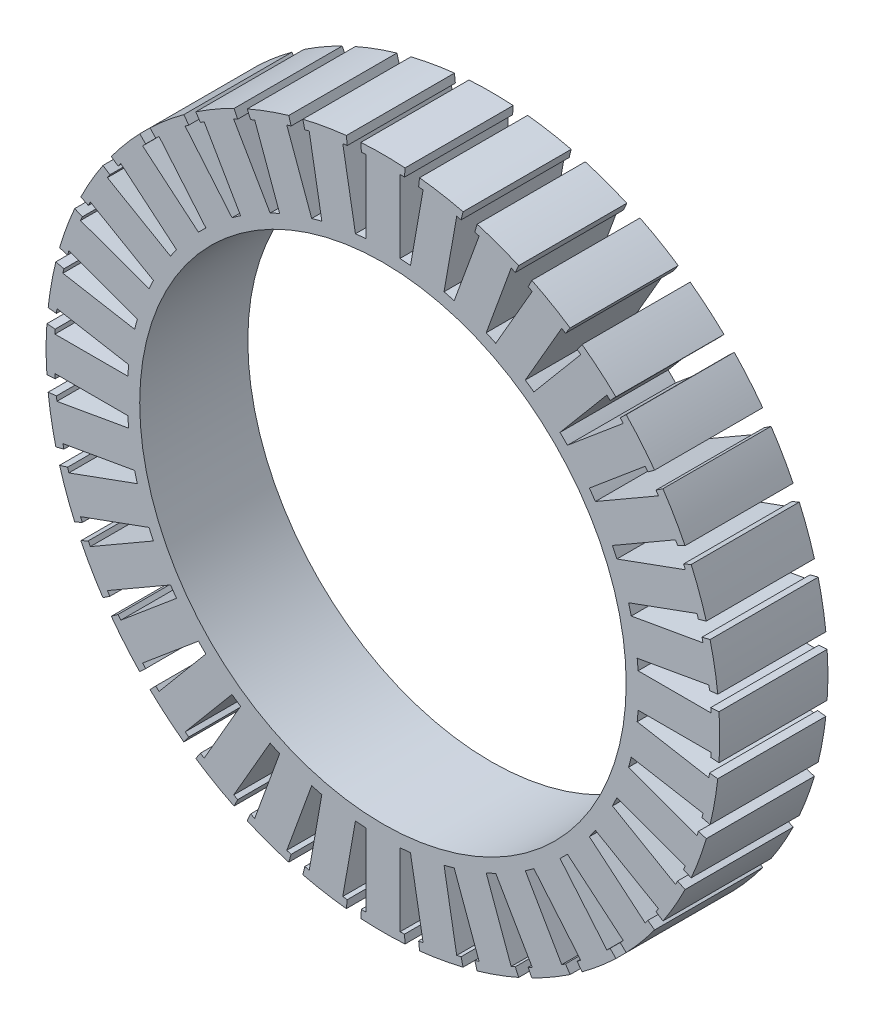
SolidWorks part; units mm, degrees
ref_plane "Front Plane" through (0, 0, 0) normal (0, 0, 1) x (1, 0, 0)
ref_plane "Top Plane" through (0, 0, 0) normal (0, 1, 0) x (1, 0, 0)
ref_plane "Right Plane" through (0, 0, 0) normal (1, 0, 0) x (0, 0, -1)
sketch "Sketch1" plane through (0, 0, 0) normal (0, 0, 1) x (1, 0, 0)
  line L0 (-2.6573, 40.4127) -> (0, 0) construction
  line L2 (-2.0508, 39.4467) -> (-2.0508, 29.178)
  line L3 (2.0508, 39.4467) -> (2.0508, 29.178)
  line L4 (2.6573, 40.4127) -> (0, 0) construction
  line L5 (-2.6573, 40.4127) -> (-2.5917, 39.4149)
  line L6 (2.6573, 40.4127) -> (2.5917, 39.4149)
  line L7 (9.6345, 39.3373) -> (9.3966, 38.366)
  line L8 (4.4007, 40.2602) -> (4.292, 39.2661)
  line L9 (4.8302, 39.2036) -> (3.047, 29.0909)
  line L10 (8.8695, 38.4913) -> (7.0864, 28.3786)
  line L11 (16.319, 37.0667) -> (15.9161, 36.1515)
  line L12 (11.3249, 38.8844) -> (11.0453, 37.9243)
  line L13 (11.5644, 37.7692) -> (8.0523, 28.1198)
  line L14 (15.4187, 36.3664) -> (11.9066, 26.7169)
  line L15 (22.5077, 33.6698) -> (21.9519, 32.8384)
  line L16 (17.9051, 36.3271) -> (17.463, 35.4301)
  line L17 (17.9473, 35.1873) -> (12.8129, 26.2943)
  line L18 (21.4994, 33.1364) -> (16.3651, 24.2435)
  line L19 (28.0124, 29.2499) -> (27.3208, 28.5276)
  line L20 (23.9412, 32.666) -> (23.35, 31.8595)
  line L21 (23.7848, 31.5362) -> (17.1842, 23.6699)
  line L22 (26.9269, 28.8997) -> (20.3263, 21.0334)
  line L23 (32.666, 23.9412) -> (31.8595, 23.35)
  line L24 (29.2499, 28.0124) -> (28.5276, 27.3208)
  line L25 (28.8997, 26.9269) -> (21.0334, 20.3263)
  line L26 (31.5362, 23.7848) -> (23.6699, 17.1842)
  line L27 (36.3271, 17.9051) -> (35.4301, 17.463)
  line L28 (33.6698, 22.5077) -> (32.8384, 21.9519)
  line L29 (33.1364, 21.4994) -> (24.2435, 16.3651)
  line L30 (35.1873, 17.9473) -> (26.2943, 12.8129)
  line L31 (38.8844, 11.3249) -> (37.9243, 11.0453)
  line L32 (37.0667, 16.319) -> (36.1515, 15.9161)
  line L33 (36.3664, 15.4187) -> (26.7169, 11.9066)
  line L34 (37.7692, 11.5644) -> (28.1198, 8.0523)
  line L35 (40.2602, 4.4007) -> (39.2661, 4.292)
  line L36 (39.3373, 9.6345) -> (38.366, 9.3966)
  line L37 (38.4913, 8.8695) -> (28.3786, 7.0864)
  line L38 (39.2036, 4.8302) -> (29.0909, 3.047)
  line L39 (40.4127, -2.6573) -> (39.4149, -2.5917)
  line L40 (40.4127, 2.6573) -> (39.4149, 2.5917)
  line L41 (39.4467, 2.0508) -> (29.178, 2.0508)
  line L42 (39.4467, -2.0508) -> (29.178, -2.0508)
  line L43 (39.3373, -9.6345) -> (38.366, -9.3966)
  line L44 (40.2602, -4.4007) -> (39.2661, -4.292)
  line L45 (39.2036, -4.8302) -> (29.0909, -3.047)
  line L46 (38.4913, -8.8695) -> (28.3786, -7.0864)
  line L47 (37.0667, -16.319) -> (36.1515, -15.9161)
  line L48 (38.8844, -11.3249) -> (37.9243, -11.0453)
  line L49 (37.7692, -11.5644) -> (28.1198, -8.0523)
  line L50 (36.3664, -15.4187) -> (26.7169, -11.9066)
  line L51 (33.6698, -22.5077) -> (32.8384, -21.9519)
  line L52 (36.3271, -17.9051) -> (35.4301, -17.463)
  line L53 (35.1873, -17.9473) -> (26.2943, -12.8129)
  line L54 (33.1364, -21.4994) -> (24.2435, -16.3651)
  line L55 (29.2499, -28.0124) -> (28.5276, -27.3208)
  line L56 (32.666, -23.9412) -> (31.8595, -23.35)
  line L57 (31.5362, -23.7848) -> (23.6699, -17.1842)
  line L58 (28.8997, -26.9269) -> (21.0334, -20.3263)
  line L59 (23.9412, -32.666) -> (23.35, -31.8595)
  line L60 (28.0124, -29.2499) -> (27.3208, -28.5276)
  line L61 (26.9269, -28.8997) -> (20.3263, -21.0334)
  line L62 (23.7848, -31.5362) -> (17.1842, -23.6699)
  line L63 (17.9051, -36.3271) -> (17.463, -35.4301)
  line L64 (22.5077, -33.6698) -> (21.9519, -32.8384)
  line L65 (21.4994, -33.1364) -> (16.3651, -24.2435)
  line L66 (17.9473, -35.1873) -> (12.8129, -26.2943)
  line L67 (11.3249, -38.8844) -> (11.0453, -37.9243)
  line L68 (16.319, -37.0667) -> (15.9161, -36.1515)
  line L69 (15.4187, -36.3664) -> (11.9066, -26.7169)
  line L70 (11.5644, -37.7692) -> (8.0523, -28.1198)
  line L71 (4.4007, -40.2602) -> (4.292, -39.2661)
  line L72 (9.6345, -39.3373) -> (9.3966, -38.366)
  line L73 (8.8695, -38.4913) -> (7.0864, -28.3786)
  line L74 (4.8302, -39.2036) -> (3.047, -29.0909)
  line L75 (-2.6573, -40.4127) -> (-2.5917, -39.4149)
  line L76 (2.6573, -40.4127) -> (2.5917, -39.4149)
  line L77 (2.0508, -39.4467) -> (2.0508, -29.178)
  line L78 (-2.0508, -39.4467) -> (-2.0508, -29.178)
  line L79 (-9.6345, -39.3373) -> (-9.3966, -38.366)
  line L80 (-4.4007, -40.2602) -> (-4.292, -39.2661)
  line L81 (-4.8302, -39.2036) -> (-3.047, -29.0909)
  line L82 (-8.8695, -38.4913) -> (-7.0864, -28.3786)
  line L83 (-16.319, -37.0667) -> (-15.9161, -36.1515)
  line L84 (-11.3249, -38.8844) -> (-11.0453, -37.9243)
  line L85 (-11.5644, -37.7692) -> (-8.0523, -28.1198)
  line L86 (-15.4187, -36.3664) -> (-11.9066, -26.7169)
  line L87 (-22.5077, -33.6698) -> (-21.9519, -32.8384)
  line L88 (-17.9051, -36.3271) -> (-17.463, -35.4301)
  line L89 (-17.9473, -35.1873) -> (-12.8129, -26.2943)
  line L90 (-21.4994, -33.1364) -> (-16.3651, -24.2435)
  line L91 (-28.0124, -29.2499) -> (-27.3208, -28.5276)
  line L92 (-23.9412, -32.666) -> (-23.35, -31.8595)
  line L93 (-23.7848, -31.5362) -> (-17.1842, -23.6699)
  line L94 (-26.9269, -28.8997) -> (-20.3263, -21.0334)
  line L95 (-32.666, -23.9412) -> (-31.8595, -23.35)
  line L96 (-29.2499, -28.0124) -> (-28.5276, -27.3208)
  line L97 (-28.8997, -26.9269) -> (-21.0334, -20.3263)
  line L98 (-31.5362, -23.7848) -> (-23.6699, -17.1842)
  line L99 (-36.3271, -17.9051) -> (-35.4301, -17.463)
  line L100 (-33.6698, -22.5077) -> (-32.8384, -21.9519)
  line L101 (-33.1364, -21.4994) -> (-24.2435, -16.3651)
  line L102 (-35.1873, -17.9473) -> (-26.2943, -12.8129)
  line L103 (-38.8844, -11.3249) -> (-37.9243, -11.0453)
  line L104 (-37.0667, -16.319) -> (-36.1515, -15.9161)
  line L105 (-36.3664, -15.4187) -> (-26.7169, -11.9066)
  line L106 (-37.7692, -11.5644) -> (-28.1198, -8.0523)
  line L107 (-40.2602, -4.4007) -> (-39.2661, -4.292)
  line L108 (-39.3373, -9.6345) -> (-38.366, -9.3966)
  line L109 (-38.4913, -8.8695) -> (-28.3786, -7.0864)
  line L110 (-39.2036, -4.8302) -> (-29.0909, -3.047)
  line L111 (-40.4127, 2.6573) -> (-39.4149, 2.5917)
  line L112 (-40.4127, -2.6573) -> (-39.4149, -2.5917)
  line L113 (-39.4467, -2.0508) -> (-29.178, -2.0508)
  line L114 (-39.4467, 2.0508) -> (-29.178, 2.0508)
  line L115 (-39.3373, 9.6345) -> (-38.366, 9.3966)
  line L116 (-40.2602, 4.4007) -> (-39.2661, 4.292)
  line L117 (-39.2036, 4.8302) -> (-29.0909, 3.047)
  line L118 (-38.4913, 8.8695) -> (-28.3786, 7.0864)
  line L119 (-37.0667, 16.319) -> (-36.1515, 15.9161)
  line L120 (-38.8844, 11.3249) -> (-37.9243, 11.0453)
  line L121 (-37.7692, 11.5644) -> (-28.1198, 8.0523)
  line L122 (-36.3664, 15.4187) -> (-26.7169, 11.9066)
  line L123 (-33.6698, 22.5077) -> (-32.8384, 21.9519)
  line L124 (-36.3271, 17.9051) -> (-35.4301, 17.463)
  line L125 (-35.1873, 17.9473) -> (-26.2943, 12.8129)
  line L126 (-33.1364, 21.4994) -> (-24.2435, 16.3651)
  line L127 (-29.2499, 28.0124) -> (-28.5276, 27.3208)
  line L128 (-32.666, 23.9412) -> (-31.8595, 23.35)
  line L129 (-31.5362, 23.7848) -> (-23.6699, 17.1842)
  line L130 (-28.8997, 26.9269) -> (-21.0334, 20.3263)
  line L131 (-23.9412, 32.666) -> (-23.35, 31.8595)
  line L132 (-28.0124, 29.2499) -> (-27.3208, 28.5276)
  line L133 (-26.9269, 28.8997) -> (-20.3263, 21.0334)
  line L134 (-23.7848, 31.5362) -> (-17.1842, 23.6699)
  line L135 (-17.9051, 36.3271) -> (-17.463, 35.4301)
  line L136 (-22.5077, 33.6698) -> (-21.9519, 32.8384)
  line L137 (-21.4994, 33.1364) -> (-16.3651, 24.2435)
  line L138 (-17.9473, 35.1873) -> (-12.8129, 26.2943)
  line L139 (-11.3249, 38.8844) -> (-11.0453, 37.9243)
  line L140 (-16.319, 37.0667) -> (-15.9161, 36.1515)
  line L141 (-15.4187, 36.3664) -> (-11.9066, 26.7169)
  line L142 (-11.5644, 37.7692) -> (-8.0523, 28.1198)
  line L143 (-4.4007, 40.2602) -> (-4.292, 39.2661)
  line L144 (-9.6345, 39.3373) -> (-9.3966, 38.366)
  line L145 (-8.8695, 38.4913) -> (-7.0864, 28.3786)
  line L146 (-4.8302, 39.2036) -> (-3.047, 29.0909)
  circle A0 centre (0, 0) radius 29.25 construction
  circle A1 centre (0, 0) radius 40.5 construction
  arc A2 (-2.6573, 40.4127) -> (2.6573, 40.4127) centre (0, 0) cw
  arc A3 (-2.0508, 29.178) -> (2.0508, 29.178) centre (0, 0) cw
  arc A4 (-2.5917, 39.4149) -> (-2.0508, 39.4467) centre (0, 0) cw
  arc A5 (2.0508, 39.4467) -> (2.5917, 39.4149) centre (0, 0) cw
  arc A6 (8.8695, 38.4913) -> (9.3966, 38.366) centre (0, 0) cw
  arc A7 (4.4007, 40.2602) -> (9.6345, 39.3373) centre (0, 0) cw
  arc A8 (4.292, 39.2661) -> (4.8302, 39.2036) centre (0, 0) cw
  arc A9 (3.047, 29.0909) -> (7.0864, 28.3786) centre (0, 0) cw
  arc A10 (15.4187, 36.3664) -> (15.9161, 36.1515) centre (0, 0) cw
  arc A11 (11.3249, 38.8844) -> (16.319, 37.0667) centre (0, 0) cw
  arc A12 (11.0453, 37.9243) -> (11.5644, 37.7692) centre (0, 0) cw
  arc A13 (8.0523, 28.1198) -> (11.9066, 26.7169) centre (0, 0) cw
  arc A14 (21.4994, 33.1364) -> (21.9519, 32.8384) centre (0, 0) cw
  arc A15 (17.9051, 36.3271) -> (22.5077, 33.6698) centre (0, 0) cw
  arc A16 (17.463, 35.4301) -> (17.9473, 35.1873) centre (0, 0) cw
  arc A17 (12.8129, 26.2943) -> (16.3651, 24.2435) centre (0, 0) cw
  arc A18 (26.9269, 28.8997) -> (27.3208, 28.5276) centre (0, 0) cw
  arc A19 (23.9412, 32.666) -> (28.0124, 29.2499) centre (0, 0) cw
  arc A20 (23.35, 31.8595) -> (23.7848, 31.5362) centre (0, 0) cw
  arc A21 (17.1842, 23.6699) -> (20.3263, 21.0334) centre (0, 0) cw
  arc A22 (31.5362, 23.7848) -> (31.8595, 23.35) centre (0, 0) cw
  arc A23 (29.2499, 28.0124) -> (32.666, 23.9412) centre (0, 0) cw
  arc A24 (28.5276, 27.3208) -> (28.8997, 26.9269) centre (0, 0) cw
  arc A25 (21.0334, 20.3263) -> (23.6699, 17.1842) centre (0, 0) cw
  arc A26 (35.1873, 17.9473) -> (35.4301, 17.463) centre (0, 0) cw
  arc A27 (33.6698, 22.5077) -> (36.3271, 17.9051) centre (0, 0) cw
  arc A28 (32.8384, 21.9519) -> (33.1364, 21.4994) centre (0, 0) cw
  arc A29 (24.2435, 16.3651) -> (26.2943, 12.8129) centre (0, 0) cw
  arc A30 (37.7692, 11.5644) -> (37.9243, 11.0453) centre (0, 0) cw
  arc A31 (37.0667, 16.319) -> (38.8844, 11.3249) centre (0, 0) cw
  arc A32 (36.1515, 15.9161) -> (36.3664, 15.4187) centre (0, 0) cw
  arc A33 (26.7169, 11.9066) -> (28.1198, 8.0523) centre (0, 0) cw
  arc A34 (39.2036, 4.8302) -> (39.2661, 4.292) centre (0, 0) cw
  arc A35 (39.3373, 9.6345) -> (40.2602, 4.4007) centre (0, 0) cw
  arc A36 (38.366, 9.3966) -> (38.4913, 8.8695) centre (0, 0) cw
  arc A37 (28.3786, 7.0864) -> (29.0909, 3.047) centre (0, 0) cw
  arc A38 (39.4467, -2.0508) -> (39.4149, -2.5917) centre (0, 0) cw
  arc A39 (40.4127, 2.6573) -> (40.4127, -2.6573) centre (0, 0) cw
  arc A40 (39.4149, 2.5917) -> (39.4467, 2.0508) centre (0, 0) cw
  arc A41 (29.178, 2.0508) -> (29.178, -2.0508) centre (0, 0) cw
  arc A42 (38.4913, -8.8695) -> (38.366, -9.3966) centre (0, 0) cw
  arc A43 (40.2602, -4.4007) -> (39.3373, -9.6345) centre (0, 0) cw
  arc A44 (39.2661, -4.292) -> (39.2036, -4.8302) centre (0, 0) cw
  arc A45 (29.0909, -3.047) -> (28.3786, -7.0864) centre (0, 0) cw
  arc A46 (36.3664, -15.4187) -> (36.1515, -15.9161) centre (0, 0) cw
  arc A47 (38.8844, -11.3249) -> (37.0667, -16.319) centre (0, 0) cw
  arc A48 (37.9243, -11.0453) -> (37.7692, -11.5644) centre (0, 0) cw
  arc A49 (28.1198, -8.0523) -> (26.7169, -11.9066) centre (0, 0) cw
  arc A50 (33.1364, -21.4994) -> (32.8384, -21.9519) centre (0, 0) cw
  arc A51 (36.3271, -17.9051) -> (33.6698, -22.5077) centre (0, 0) cw
  arc A52 (35.4301, -17.463) -> (35.1873, -17.9473) centre (0, 0) cw
  arc A53 (26.2943, -12.8129) -> (24.2435, -16.3651) centre (0, 0) cw
  arc A54 (28.8997, -26.9269) -> (28.5276, -27.3208) centre (0, 0) cw
  arc A55 (32.666, -23.9412) -> (29.2499, -28.0124) centre (0, 0) cw
  arc A56 (31.8595, -23.35) -> (31.5362, -23.7848) centre (0, 0) cw
  arc A57 (23.6699, -17.1842) -> (21.0334, -20.3263) centre (0, 0) cw
  arc A58 (23.7848, -31.5362) -> (23.35, -31.8595) centre (0, 0) cw
  arc A59 (28.0124, -29.2499) -> (23.9412, -32.666) centre (0, 0) cw
  arc A60 (27.3208, -28.5276) -> (26.9269, -28.8997) centre (0, 0) cw
  arc A61 (20.3263, -21.0334) -> (17.1842, -23.6699) centre (0, 0) cw
  arc A62 (17.9473, -35.1873) -> (17.463, -35.4301) centre (0, 0) cw
  arc A63 (22.5077, -33.6698) -> (17.9051, -36.3271) centre (0, 0) cw
  arc A64 (21.9519, -32.8384) -> (21.4994, -33.1364) centre (0, 0) cw
  arc A65 (16.3651, -24.2435) -> (12.8129, -26.2943) centre (0, 0) cw
  arc A66 (11.5644, -37.7692) -> (11.0453, -37.9243) centre (0, 0) cw
  arc A67 (16.319, -37.0667) -> (11.3249, -38.8844) centre (0, 0) cw
  arc A68 (15.9161, -36.1515) -> (15.4187, -36.3664) centre (0, 0) cw
  arc A69 (11.9066, -26.7169) -> (8.0523, -28.1198) centre (0, 0) cw
  arc A70 (4.8302, -39.2036) -> (4.292, -39.2661) centre (0, 0) cw
  arc A71 (9.6345, -39.3373) -> (4.4007, -40.2602) centre (0, 0) cw
  arc A72 (9.3966, -38.366) -> (8.8695, -38.4913) centre (0, 0) cw
  arc A73 (7.0864, -28.3786) -> (3.047, -29.0909) centre (0, 0) cw
  arc A74 (-2.0508, -39.4467) -> (-2.5917, -39.4149) centre (0, 0) cw
  arc A75 (2.6573, -40.4127) -> (-2.6573, -40.4127) centre (0, 0) cw
  arc A76 (2.5917, -39.4149) -> (2.0508, -39.4467) centre (0, 0) cw
  arc A77 (2.0508, -29.178) -> (-2.0508, -29.178) centre (0, 0) cw
  arc A78 (-8.8695, -38.4913) -> (-9.3966, -38.366) centre (0, 0) cw
  arc A79 (-4.4007, -40.2602) -> (-9.6345, -39.3373) centre (0, 0) cw
  arc A80 (-4.292, -39.2661) -> (-4.8302, -39.2036) centre (0, 0) cw
  arc A81 (-3.047, -29.0909) -> (-7.0864, -28.3786) centre (0, 0) cw
  arc A82 (-15.4187, -36.3664) -> (-15.9161, -36.1515) centre (0, 0) cw
  arc A83 (-11.3249, -38.8844) -> (-16.319, -37.0667) centre (0, 0) cw
  arc A84 (-11.0453, -37.9243) -> (-11.5644, -37.7692) centre (0, 0) cw
  arc A85 (-8.0523, -28.1198) -> (-11.9066, -26.7169) centre (0, 0) cw
  arc A86 (-21.4994, -33.1364) -> (-21.9519, -32.8384) centre (0, 0) cw
  arc A87 (-17.9051, -36.3271) -> (-22.5077, -33.6698) centre (0, 0) cw
  arc A88 (-17.463, -35.4301) -> (-17.9473, -35.1873) centre (0, 0) cw
  arc A89 (-12.8129, -26.2943) -> (-16.3651, -24.2435) centre (0, 0) cw
  arc A90 (-26.9269, -28.8997) -> (-27.3208, -28.5276) centre (0, 0) cw
  arc A91 (-23.9412, -32.666) -> (-28.0124, -29.2499) centre (0, 0) cw
  arc A92 (-23.35, -31.8595) -> (-23.7848, -31.5362) centre (0, 0) cw
  arc A93 (-17.1842, -23.6699) -> (-20.3263, -21.0334) centre (0, 0) cw
  arc A94 (-31.5362, -23.7848) -> (-31.8595, -23.35) centre (0, 0) cw
  arc A95 (-29.2499, -28.0124) -> (-32.666, -23.9412) centre (0, 0) cw
  arc A96 (-28.5276, -27.3208) -> (-28.8997, -26.9269) centre (0, 0) cw
  arc A97 (-21.0334, -20.3263) -> (-23.6699, -17.1842) centre (0, 0) cw
  arc A98 (-35.1873, -17.9473) -> (-35.4301, -17.463) centre (0, 0) cw
  arc A99 (-33.6698, -22.5077) -> (-36.3271, -17.9051) centre (0, 0) cw
  arc A100 (-32.8384, -21.9519) -> (-33.1364, -21.4994) centre (0, 0) cw
  arc A101 (-24.2435, -16.3651) -> (-26.2943, -12.8129) centre (0, 0) cw
  arc A102 (-37.7692, -11.5644) -> (-37.9243, -11.0453) centre (0, 0) cw
  arc A103 (-37.0667, -16.319) -> (-38.8844, -11.3249) centre (0, 0) cw
  arc A104 (-36.1515, -15.9161) -> (-36.3664, -15.4187) centre (0, 0) cw
  arc A105 (-26.7169, -11.9066) -> (-28.1198, -8.0523) centre (0, 0) cw
  arc A106 (-39.2036, -4.8302) -> (-39.2661, -4.292) centre (0, 0) cw
  arc A107 (-39.3373, -9.6345) -> (-40.2602, -4.4007) centre (0, 0) cw
  arc A108 (-38.366, -9.3966) -> (-38.4913, -8.8695) centre (0, 0) cw
  arc A109 (-28.3786, -7.0864) -> (-29.0909, -3.047) centre (0, 0) cw
  arc A110 (-39.4467, 2.0508) -> (-39.4149, 2.5917) centre (0, 0) cw
  arc A111 (-40.4127, -2.6573) -> (-40.4127, 2.6573) centre (0, 0) cw
  arc A112 (-39.4149, -2.5917) -> (-39.4467, -2.0508) centre (0, 0) cw
  arc A113 (-29.178, -2.0508) -> (-29.178, 2.0508) centre (0, 0) cw
  arc A114 (-38.4913, 8.8695) -> (-38.366, 9.3966) centre (0, 0) cw
  arc A115 (-40.2602, 4.4007) -> (-39.3373, 9.6345) centre (0, 0) cw
  arc A116 (-39.2661, 4.292) -> (-39.2036, 4.8302) centre (0, 0) cw
  arc A117 (-29.0909, 3.047) -> (-28.3786, 7.0864) centre (0, 0) cw
  arc A118 (-36.3664, 15.4187) -> (-36.1515, 15.9161) centre (0, 0) cw
  arc A119 (-38.8844, 11.3249) -> (-37.0667, 16.319) centre (0, 0) cw
  arc A120 (-37.9243, 11.0453) -> (-37.7692, 11.5644) centre (0, 0) cw
  arc A121 (-28.1198, 8.0523) -> (-26.7169, 11.9066) centre (0, 0) cw
  arc A122 (-33.1364, 21.4994) -> (-32.8384, 21.9519) centre (0, 0) cw
  arc A123 (-36.3271, 17.9051) -> (-33.6698, 22.5077) centre (0, 0) cw
  arc A124 (-35.4301, 17.463) -> (-35.1873, 17.9473) centre (0, 0) cw
  arc A125 (-26.2943, 12.8129) -> (-24.2435, 16.3651) centre (0, 0) cw
  arc A126 (-28.8997, 26.9269) -> (-28.5276, 27.3208) centre (0, 0) cw
  arc A127 (-32.666, 23.9412) -> (-29.2499, 28.0124) centre (0, 0) cw
  arc A128 (-31.8595, 23.35) -> (-31.5362, 23.7848) centre (0, 0) cw
  arc A129 (-23.6699, 17.1842) -> (-21.0334, 20.3263) centre (0, 0) cw
  arc A130 (-23.7848, 31.5362) -> (-23.35, 31.8595) centre (0, 0) cw
  arc A131 (-28.0124, 29.2499) -> (-23.9412, 32.666) centre (0, 0) cw
  arc A132 (-27.3208, 28.5276) -> (-26.9269, 28.8997) centre (0, 0) cw
  arc A133 (-20.3263, 21.0334) -> (-17.1842, 23.6699) centre (0, 0) cw
  arc A134 (-17.9473, 35.1873) -> (-17.463, 35.4301) centre (0, 0) cw
  arc A135 (-22.5077, 33.6698) -> (-17.9051, 36.3271) centre (0, 0) cw
  arc A136 (-21.9519, 32.8384) -> (-21.4994, 33.1364) centre (0, 0) cw
  arc A137 (-16.3651, 24.2435) -> (-12.8129, 26.2943) centre (0, 0) cw
  arc A138 (-11.5644, 37.7692) -> (-11.0453, 37.9243) centre (0, 0) cw
  arc A139 (-16.319, 37.0667) -> (-11.3249, 38.8844) centre (0, 0) cw
  arc A140 (-15.9161, 36.1515) -> (-15.4187, 36.3664) centre (0, 0) cw
  arc A141 (-11.9066, 26.7169) -> (-8.0523, 28.1198) centre (0, 0) cw
  arc A142 (-4.8302, 39.2036) -> (-4.292, 39.2661) centre (0, 0) cw
  arc A143 (-9.6345, 39.3373) -> (-4.4007, 40.2602) centre (0, 0) cw
  arc A144 (-9.3966, 38.366) -> (-8.8695, 38.4913) centre (0, 0) cw
  arc A145 (-7.0864, 28.3786) -> (-3.047, 29.0909) centre (0, 0) cw
  point P296 (0, 0)
  dimension "D1" = 58.5
  dimension "D2" = 81
  dimension "D4" = 1.75
  dimension "D5" = 1
  dimension "D6" = 1
  dimension "D3" = 36
sketch "Sketch2" plane through (0, 0, 0) normal (0, 0, 1) x (1, 0, 0)
  circle A0 centre (0, 0) radius 29.25 construction
  circle A1 centre (0, 0) radius 29.25
  circle A2 centre (0, 0) radius 30.75
  dimension "D1" = 1.5
extrude "Boss-Extrude2" add sketch "Sketch1" along normal mid plane 13
extrude "Boss-Extrude3" add sketch "Sketch2" along normal mid plane 13
